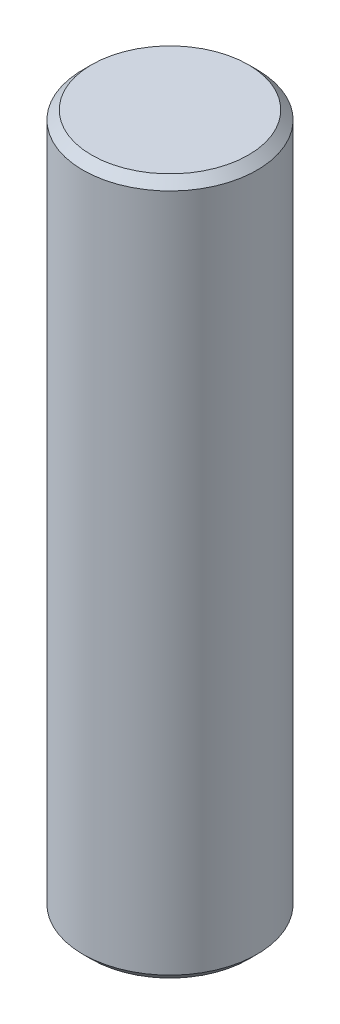
SolidWorks part; units mm, degrees
ref_plane "Front Plane" through (0, 0, 0) normal (0, 0, 1) x (1, 0, 0)
ref_plane "Top Plane" through (0, 0, 0) normal (0, 1, 0) x (1, 0, 0)
ref_plane "Right Plane" through (0, 0, 0) normal (1, 0, 0) x (0, 0, -1)
sketch "Sketch1" plane through (0, 0, 0) normal (0, 1, 0) x (1, 0, 0)
  circle A0 centre (0, 0) radius 1
extrude "Boss-Extrude1" add sketch "Sketch1" along normal mid plane 8
chamfer "Chamfer1" distance 0.1 angle 45 2 edges at (0, -4, 1) (0, 4, 1)
